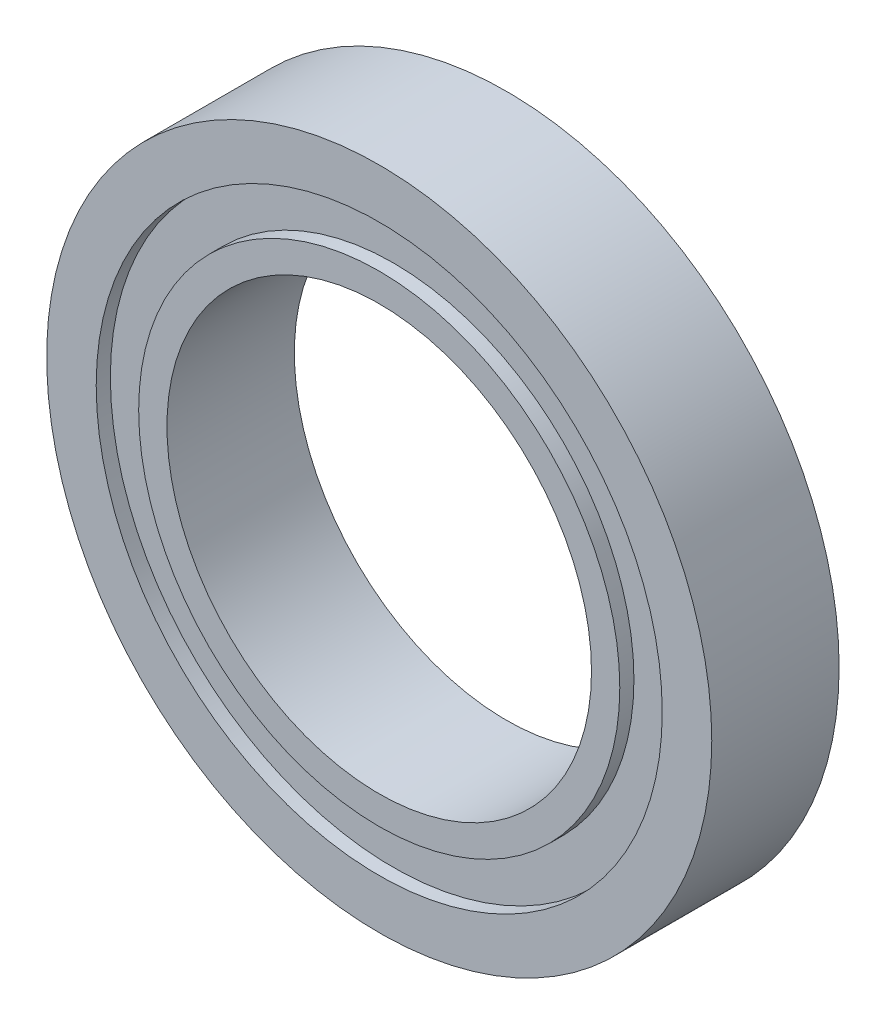
SolidWorks part; units mm, degrees
ref_plane "前视基准面" through (0, 0, 0) normal (0, 0, 1) x (1, 0, 0)
ref_plane "上视基准面" through (0, 0, 0) normal (0, 1, 0) x (1, 0, 0)
ref_plane "右视基准面" through (0, 0, 0) normal (1, 0, 0) x (0, 0, -1)
sketch "草图1" plane through (0, 0, 0) normal (0, 0, 1) x (1, 0, 0)
  circle A0 centre (0, 0) radius 15
  circle A1 centre (0, 0) radius 23.5
  dimension "D1" = 30
  dimension "D2" = 47
extrude "凸台-拉伸1" add sketch "草图1" along normal blind 9
sketch "草图2" plane through (0, 0, 9) normal (0, 0, 1) x (1, 0, 0)
  circle A0 centre (0, 0) radius 17
  circle A1 centre (0, 0) radius 20
extrude "切除-拉伸1" cut sketch "草图2" against normal blind 1
